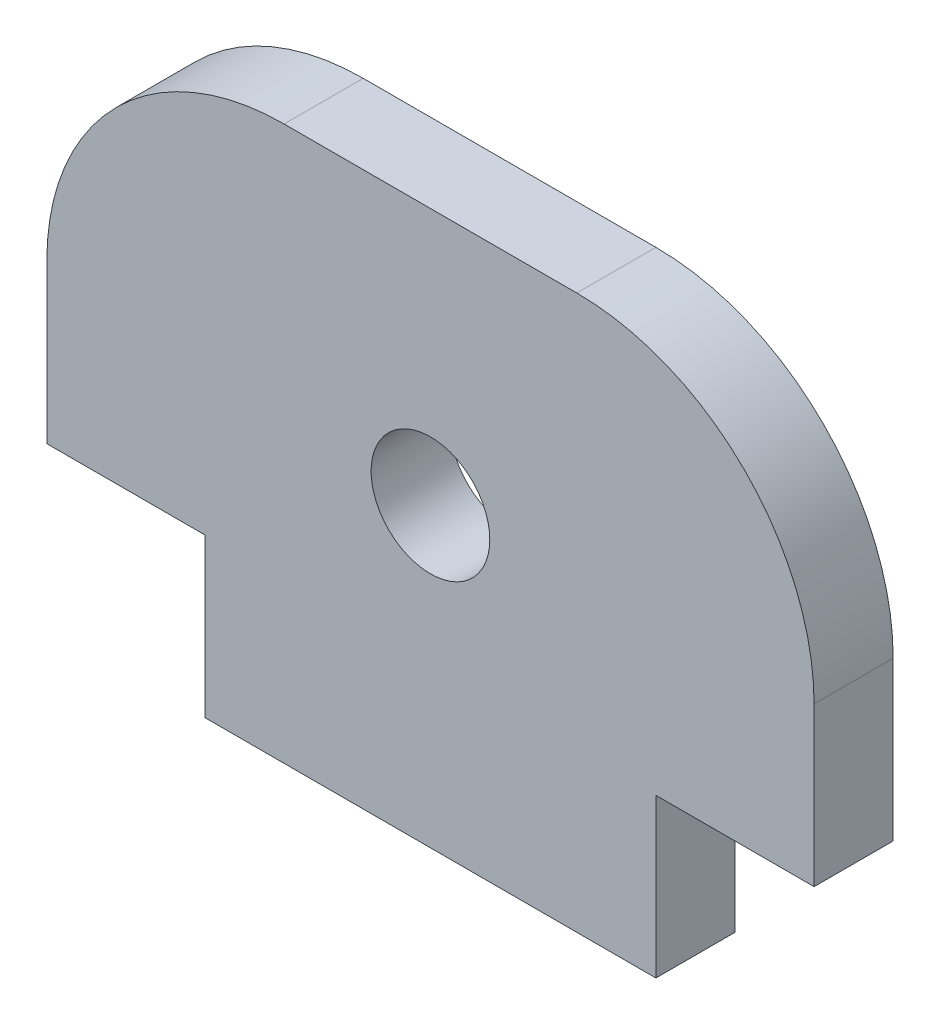
SolidWorks part; units mm, degrees
material "Acrylic (Medium-high impact)"
ref_plane "Front Plane" through (0, 0, 0) normal (0, 0, 1) x (1, 0, 0)
ref_plane "Top Plane" through (0, 0, 0) normal (0, 1, 0) x (1, 0, 0)
ref_plane "Right Plane" through (0, 0, 0) normal (1, 0, 0) x (0, 0, -1)
sketch "Model" plane through (0, 0, 0) normal (0, 0, 1) x (1, 0, 0)
  line L100 (2118.4945, 1218.2986) -> (2118.4945, 1222.2986)
  line L101 (2099.0945, 1218.2986) -> (2099.0945, 1222.2986)
  line L102 (2099.0945, 1218.2986) -> (2103.0945, 1218.2986)
  line L103 (2118.4945, 1218.2986) -> (2114.4945, 1218.2986)
  line L104 (2105.0945, 1228.2986) -> (2112.4945, 1228.2986)
  line L582 (2114.4945, 1218.2986) -> (2114.4945, 1214.2986)
  line L583 (2114.4945, 1214.2986) -> (2103.0945, 1214.2986)
  line L584 (2103.0945, 1214.2986) -> (2103.0945, 1218.2986)
  arc A49 (2118.4945, 1222.2986) -> (2112.4945, 1228.2986) centre (2112.4945, 1222.2986) ccw
  arc A50 (2105.0945, 1228.2986) -> (2099.0945, 1222.2986) centre (2105.0945, 1222.2986) ccw
  circle A53 centre (2108.7945, 1221.7986) radius 1.5
extrude "Boss-Extrude1" add sketch "Model" along normal blind 2
